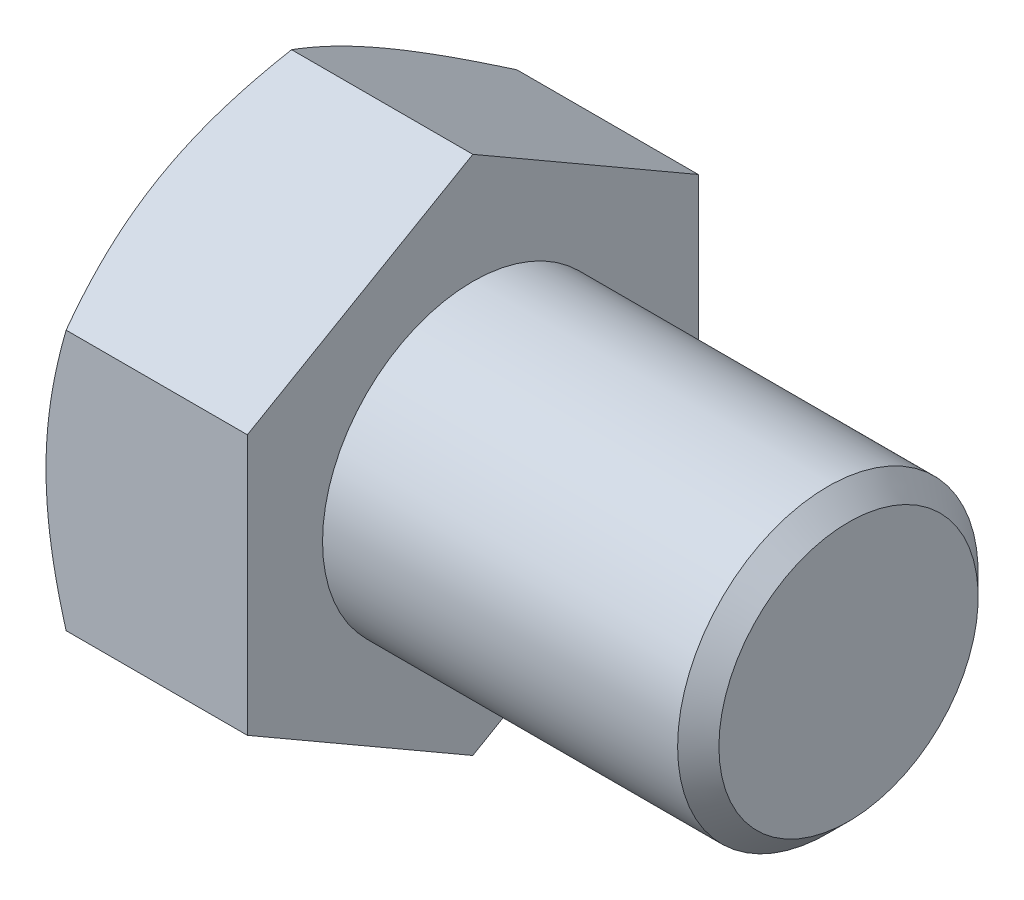
SolidWorks part; units mm, degrees
extrude "BaseHead" add sketch "Sketch1" along normal blind 13.4
sketch "Sketch1" plane through (0, 0, 0) normal (1, 0, 0) x (0, 0, -1)
  line L0 (15, 8.6603) -> (15, -8.6603)
  line L1 (-15, 8.6603) -> (-15, -8.6603)
  line L2 (15, -8.6603) -> (0, -17.3205)
  line L3 (0, -17.3205) -> (-15, -8.6603)
  line L4 (15, 8.6603) -> (0, 17.3205)
  line L5 (0, 17.3205) -> (-15, 8.6603)
  dimension "Width_flats" = 30
  dimension "D2" = 120
  dimension "D3" = 15
  dimension "D4" = 15
  dimension "D5" = 15
material "Dacromet"
ref_plane "Plane1" through (0, 0, 0) normal (0, 0, 1) x (1, 0, 0)
ref_plane "Plane2" through (0, 0, 0) normal (0, 1, 0) x (1, 0, 0)
ref_plane "Plane3" through (0, 0, 0) normal (1, 0, 0) x (0, 0, -1)
sketch "BodySke" plane through (0, 0, 0) normal (0, 0, 1) x (1, 0, 0)
  line L0 (0, 8.6603) -> (0, -8.6603) construction
  line L1 (0, 0) -> (38.4, 0)
  line L2 (0, 0) -> (0, 10)
  line L3 (0, 10) -> (37.026, 10)
  line L4 (38.4, 0) -> (38.4, 8.626)
  line L5 (13.4, 17.3205) -> (13.4, 8.6603) construction
  line L6 (38.4, 8.626) -> (37.026, 10)
  line L7 (0, 0) -> (96.52, 0) construction
  line L8 (38.4, -8.626) -> (37.026, -10) construction
  line L9 (0, -10) -> (37.026, -10) construction
  line L10 (15.9, 15.24) -> (15.9, -1.27) construction
  line L11 (-7.6, 15.24) -> (-7.6, -1.27) construction
  line L12 (13.4, 8.6603) -> (13.4, -8.6603) construction
  dimension "Diameter" = 20
  dimension "Advance" = 2.5
revolve "BaseBody" add sketch "BodySke"
cosmetic thread "ThreadCosmetic" [suppressed]
fillet "HeadFillet" [suppressed] radius 0.8
sketch "Sketch3" plane through (0, 0, 0) normal (0, 0, 1) x (1, 0, 0)
  line L0 (0, 15) -> (4.2265, 22.3205)
  line L1 (0, 17.3205) -> (0, 8.6603) construction
  line L2 (4.2265, 22.3205) -> (4.2265, 27.3205)
  line L3 (4.2265, 27.3205) -> (-10, 27.3205)
  line L4 (-10, 27.3205) -> (-10, 15)
  line L5 (-10, 15) -> (0, 15)
  line L6 (0, 0) -> (99.06, 0) construction
  line L7 (13.4, 17.3205) -> (0, 17.3205) construction
  dimension "D1" = 15
  dimension "D2" = 5
  dimension "D3" = 10
  dimension "D4" = 5
  dimension "Head_ch_ang" = 30
revolve "HeadChamfer" cut sketch "Sketch3" angle 360 about L6
sketch "ThdSchSke" plane through (0, 0, 0) normal (0, 0, 1) x (1, 0, 0)
  line L0 (15.9, -8.626) -> (14.9379, -10)
  line L1 (15.9, -8.626) -> (16.8621, -10)
  line L2 (16.8621, -10) -> (16.8621, -12.5)
  line L3 (-3.175, 0) -> (5.1513, 0) construction
  line L5 (16.8621, -12.5) -> (14.9379, -12.5)
  line L6 (14.9379, -12.5) -> (14.9379, -10)
  dimension "Thread_minor" = 17.252
  dimension "Diameter" = 20
  dimension "Start" = 15.9
revolve "ThreadSchematic" [suppressed] cut sketch "ThdSchSke" angle 360 about L3
pattern_linear "ThdSchPat" [suppressed]
equation "\"D3@Sketch1\" = \"Width_flats@Sketch1\" / 2"
equation "\"D4@Sketch1\" = \"D3@Sketch1\""
equation "\"D5@Sketch1\" = \"D4@Sketch1\""
equation "\"Thread_minor@ThreadCosmetic\" = \"Minor_dia@BodySke\""
equation "\"D1@Sketch3\" = \"Width_flats@Sketch1\" / 2"
equation "' \"D1@Sketch4\" = \"Width_flats@Sketch1\""
equation "\"Thread_length@ThreadCosmetic\" = ((sgn( (\"Length@BodySke\" - \"Advance@BodySke\" ) - \"Thread_nom@BodySke\" )-1)*( (\"Length@BodySke\" - \"Advance@BodySke\" ) - \"Thread_nom@BodySke\" ))/-2+ \"Thread_nom@BodySke\""
equation "\"Thread_minor@ThdSchSke\" = \"Minor_dia@BodySke\""
equation "\"Diameter@ThdSchSke\" = \"Diameter@BodySke\""
equation "\"Overcut@ThdSchSke\" = \"Diameter@BodySke\" * 1.25"
equation "\"Start@ThdSchSke\" = \"Head_ht@BaseHead\" + \"Length@BodySke\" - \"Thread_length@ThreadCosmetic\"  '---Non-countersunk---"
equation "\"Num_threads@ThdSchPat\" = int( \"Thread_length@ThreadCosmetic\" / \"Advance@BodySke\" + 0.999 )  + 1"
equation "\"Advance@ThdSchPat\" = \"Thread_length@ThreadCosmetic\" /  (\"Num_threads@ThdSchPat\" - 1) 'relax it"
equation "\"Num_threads@ThdSchPat\" = \"Num_threads@ThdSchPat\" - sgn( \"Num_threads@ThdSchPat\" - 1) '---chamfered tips only---"
